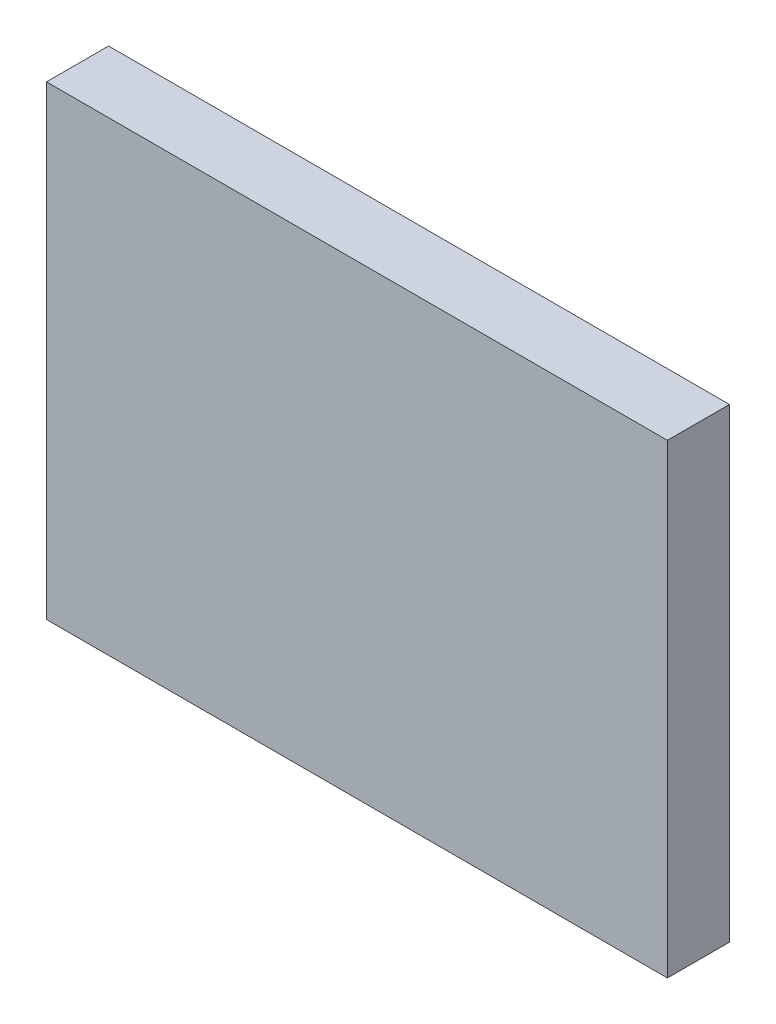
SolidWorks part; units mm, degrees
ref_plane "Front Plane" through (0, 0, 0) normal (0, 0, 1) x (1, 0, 0)
ref_plane "Top Plane" through (0, 0, 0) normal (0, 1, 0) x (1, 0, 0)
ref_plane "Right Plane" through (0, 0, 0) normal (1, 0, 0) x (0, 0, -1)
sketch "Sketch1" plane through (0, 0, 0) normal (0, 0, 1) x (1, 0, 0)
  line L1 (10, -7.5) -> (-10, -7.5)
  line L2 (10, -7.5) -> (10, 7.5)
  line L3 (10, 7.5) -> (-10, 7.5)
  line L4 (-10, -7.5) -> (-10, 7.5)
  line L5 (10, -7.5) -> (-10, 7.5) construction
  line L6 (10, 7.5) -> (-10, -7.5) construction
  point P0 (0, 0)
  dimension "D1" = 20
  dimension "D2" = 15
extrude "Boss-Extrude1" add sketch "Sketch1" along normal blind 2
